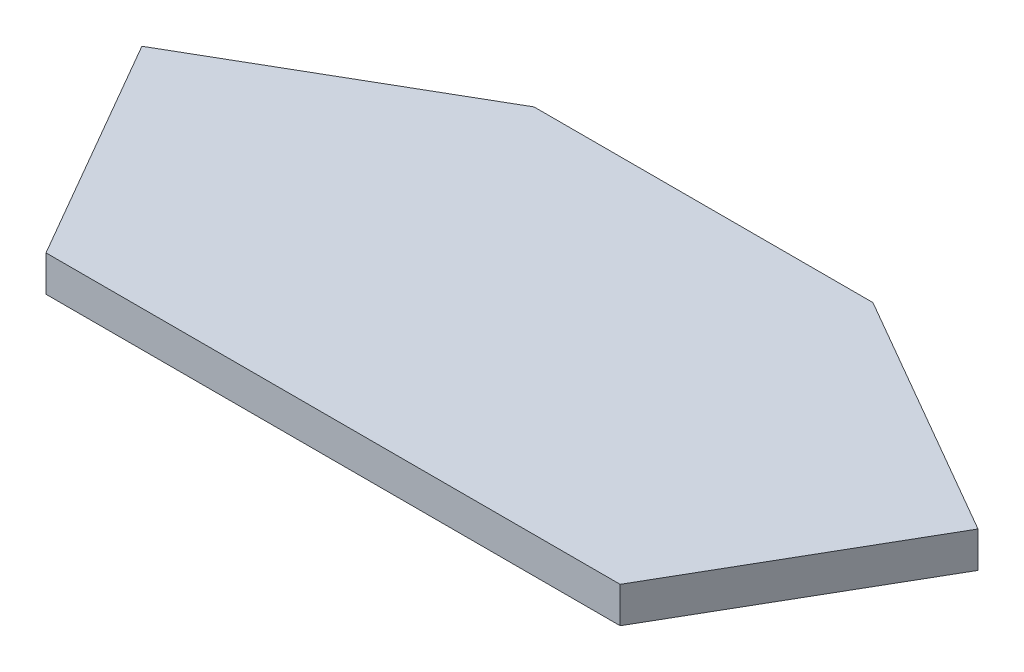
SolidWorks part; units mm, degrees
ref_plane "Front Plane" through (0, 0, 0) normal (0, 0, 1) x (1, 0, 0)
ref_plane "Top Plane" through (0, 0, 0) normal (0, 1, 0) x (1, 0, 0)
ref_plane "Right Plane" through (0, 0, 0) normal (1, 0, 0) x (0, 0, -1)
sketch "Sketch1" plane through (0, 0, 0) normal (0, 1, 0) x (1, 0, 0)
  line L0 (-80, 0) -> (80, 0)
  line L1 (80, 0) -> (116.5, 63.2199)
  line L2 (116.5, 63.2199) -> (47.218, 103.2199)
  line L3 (47.218, 103.2199) -> (-47.218, 103.2199)
  line L4 (0, 103.2199) -> (0, 0) construction
  line L5 (-80, 0) -> (-116.5, 63.2199)
  line L6 (-116.5, 63.2199) -> (-47.218, 103.2199)
  point P3 (0, 0)
  dimension "D1" = 0
  dimension "D2" = 80
  dimension "D3" = 94.4359
  dimension "D4" = 80
  dimension "D5" = 0
  dimension "D7" = 120
extrude "Boss-Extrude1" add sketch "Sketch1" along normal blind 10
